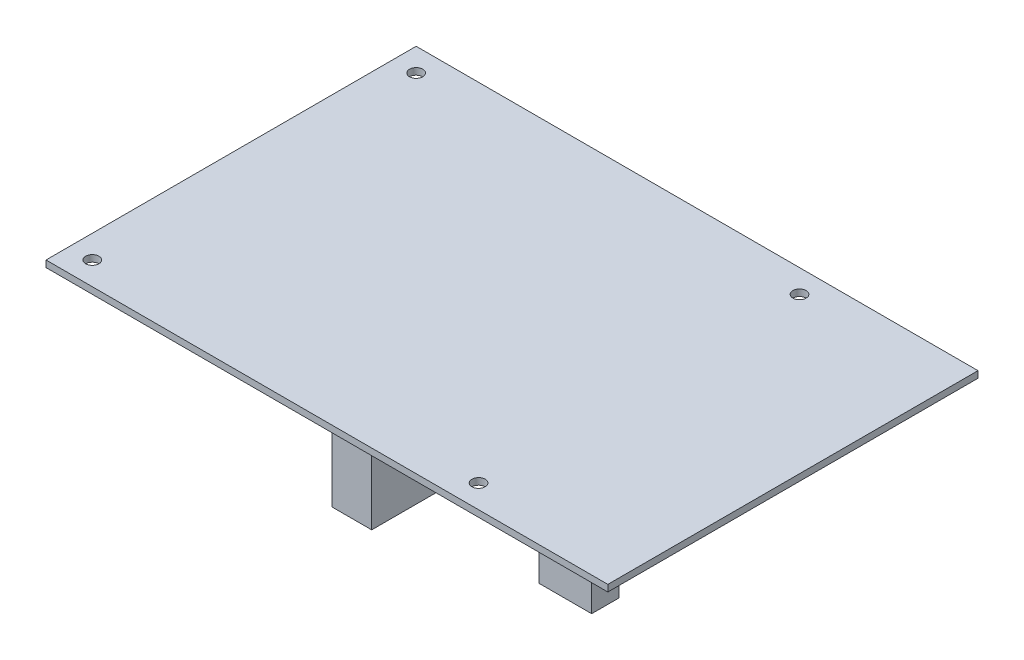
SolidWorks part; units mm, degrees
ref_plane "Plan de face" through (0, 0, 0) normal (0, 0, 1) x (1, 0, 0)
ref_plane "Plan de dessus" through (0, 0, 0) normal (0, 1, 0) x (1, 0, 0)
ref_plane "Plan de droite" through (0, 0, 0) normal (1, 0, 0) x (0, 0, -1)
sketch "Esquisse1" plane through (0, 0, 0) normal (0, 1, 0) x (1, 0, 0)
  line L0 (-93.8076, -10.8043) -> (81.5049, -10.8043) construction
  line L1 (-32.574, 17.1957) -> (52.426, 17.1957)
  line L2 (-32.574, 17.1957) -> (-32.574, -38.8043)
  line L3 (-32.574, -38.8043) -> (52.426, -38.8043)
  line L4 (52.426, 17.1957) -> (52.426, -38.8043)
  circle A0 centre (-29.074, 13.6957) radius 1
  circle A1 centre (28.926, 13.6957) radius 1
  circle A2 centre (29.3635, -35.3043) radius 1
  circle A3 centre (-29.074, -35.3043) radius 1
  point P14 (0, 0)
  point P15 (0, 0)
  dimension "D3" = 2
  dimension "D4" = 2
  dimension "D5" = 2
  dimension "D6" = 2
  dimension "D1" = 85
  dimension "D2" = 56
  dimension "D7" = 58
  dimension "D8" = 49
  dimension "D9" = 3.5
extrude "Boss.-Extru.1" add sketch "Esquisse1" along normal blind 1
sketch "Esquisse2" plane through (0, 0, 0) normal (0, -1, 0) x (1, 0, 0)
  line L0 (-6.574, 26.5414) -> (-6.574, -7.8541) construction
  line L1 (-9.574, 18.5315) -> (-3.574, 18.5315)
  line L2 (-9.574, 18.5315) -> (-9.574, 3.0771)
  line L3 (-9.574, 3.0771) -> (-3.574, 3.0771)
  line L4 (-3.574, 18.5315) -> (-3.574, 3.0771)
  line L5 (-32.574, -17.1957) -> (-32.574, 38.8043) construction
  line L6 (-44.8241, 10.8043) -> (72.1206, 10.8043) construction
  line L7 (-32.574, 38.8043) -> (52.426, 38.8043) construction
  line L8 (52.426, -17.1957) -> (-32.574, -17.1957) construction
  line L10 (16.0512, 12.8774) -> (24.0512, 12.8774)
  line L11 (16.0512, 12.8774) -> (16.0512, 8.7311)
  line L12 (16.0512, 8.7311) -> (24.0512, 8.7311)
  line L13 (24.0512, 12.8774) -> (24.0512, 8.7311)
  dimension "D1" = 6
  dimension "D2" = 26
  dimension "D3" = 8
extrude "Boss.-Extru.2" add sketch "Esquisse2" along normal blind 30
fillet "Congé1" radius 5 8 edges at (20.0512, 0, 12.8774) (24.0512, 0, 10.8043) (16.0512, 0, 10.8043) (20.0512, 0, 8.7311) (-6.574, 0, 3.0771) (-9.574, 0, 10.8043) (-3.574, 0, 10.8043) (-6.574, 0, 18.5315)
sketch "Esquisse3" plane through (0, -30, 0) normal (0, -1, 0) x (1, 0, 0)
  line L0 (-6.574, -2.7654) -> (-6.574, 24.2798) construction
  line L1 (-3.574, 3.0771) -> (-3.574, 18.5315) construction
  line L2 (-9.574, 18.5315) -> (-9.574, 3.0771) construction
  line L3 (-17.4946, 10.8043) -> (4.1061, 10.8043) construction
  line L4 (-32.574, 38.8043) -> (52.426, 38.8043) construction
  line L5 (52.426, -17.1957) -> (-32.574, -17.1957) construction
  circle A0 centre (-6.574, 14.3043) radius 0.85
  circle A1 centre (-6.574, 7.3043) radius 0.85
  point P16 (0, 0)
  dimension "D1" = 1.7
  dimension "D2" = 1.7
  dimension "D3" = 7
extrude "Enlèv. mat.-Extru.1" cut sketch "Esquisse3" against normal blind 5
